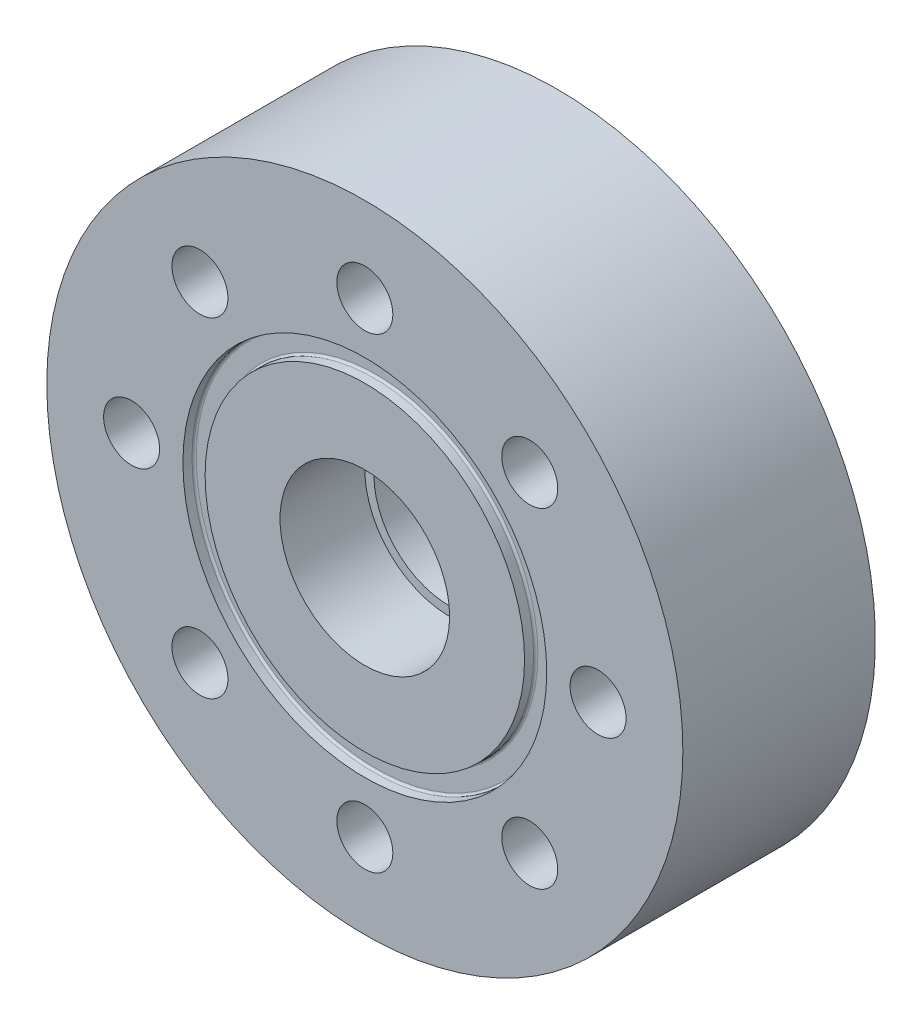
SolidWorks part; units mm, degrees
ref_plane "Front Plane" through (0, 0, 0) normal (0, 0, 1) x (1, 0, 0)
ref_plane "Top Plane" through (0, 0, 0) normal (0, 1, 0) x (1, 0, 0)
ref_plane "Right Plane" through (0, 0, 0) normal (1, 0, 0) x (0, 0, -1)
sketch "Sketch2" plane through (0, 0, 0) normal (0, 0, 1) x (1, 0, 0)
  circle A0 centre (0, 0) radius 10
  circle A1 centre (0, 0) radius 37.5
  dimension "D1" = 20
  dimension "D2" = 0
  dimension "D3" = 75
extrude "Boss-Extrude1" add sketch "Sketch2" along normal blind 10
sketch "Sketch5" plane through (0, 0, 0) normal (1, 0, 0) x (0, 0, -1)
  line L0 (-10, 0) -> (1.2709, 0) construction
  line L1 (-10, 37.5) -> (-10, -37.5) construction
sketch "Sketch7" plane through (0, 0, 0) normal (0, 0, -1) x (-1, 0, 0)
  circle A0 centre (0, 0) radius 37.5
  dimension "D1" = 75
extrude "Boss-Extrude2" add sketch "Sketch7" along normal blind 12.7
sketch "Sketch8" plane through (0, 0, 10) normal (0, 0, 1) x (1, 0, 0)
  circle A0 centre (0, 0) radius 27.5
  circle A1 centre (0, 27.5) radius 3.302
  circle A2 centre (19.4454, 19.4454) radius 3.302
  circle A3 centre (27.5, 0) radius 3.302
  circle A4 centre (19.4454, -19.4454) radius 3.302
  circle A5 centre (0, -27.5) radius 3.302
  circle A6 centre (-19.4454, -19.4454) radius 3.302
  circle A7 centre (-27.5, 0) radius 3.302
  circle A8 centre (-19.4454, 19.4454) radius 3.302
  point P21 (0, 0)
  dimension "D1" = 55
  dimension "D2" = 6.604
  dimension "D3" = 8
extrude "Cut-Extrude2" cut sketch "Sketch8" against normal through all contours A0 A8 | A0 A8 | A0 A7 | A0 A7 | A0 A6 | A0 A6 | A0 A5 | A0 A4 | A0 A4 | A0 A3 | A0 A3 | A0 A2 | A0 A2 | A0 A1 | A0 A1
sketch "Sketch9" plane through (0, 0, -12.7) normal (0, 0, -1) x (-1, 0, 0)
  circle A0 centre (0, 0) radius 8.9297
  dimension "D1" = 17.8594
extrude "Cut-Extrude3" cut sketch "Sketch9" against normal blind 12.7
sketch "Sketch11" plane through (0, 0, 10) normal (0, 0, 1) x (1, 0, 0)
  circle A0 centre (0, 0) radius 21.45
  circle A1 centre (0, 0) radius 18.8338
  dimension "D1" = 42.9
  dimension "D2" = 2.6162
extrude "Cut-Extrude5" cut sketch "Sketch11" along direction (0, 0, 1) on the side against the normal blind 1.3208
fillet "Fillet1" radius 0.254 2 edges at (18.8338, 0, 8.6792) (21.45, 0, 8.6792)
